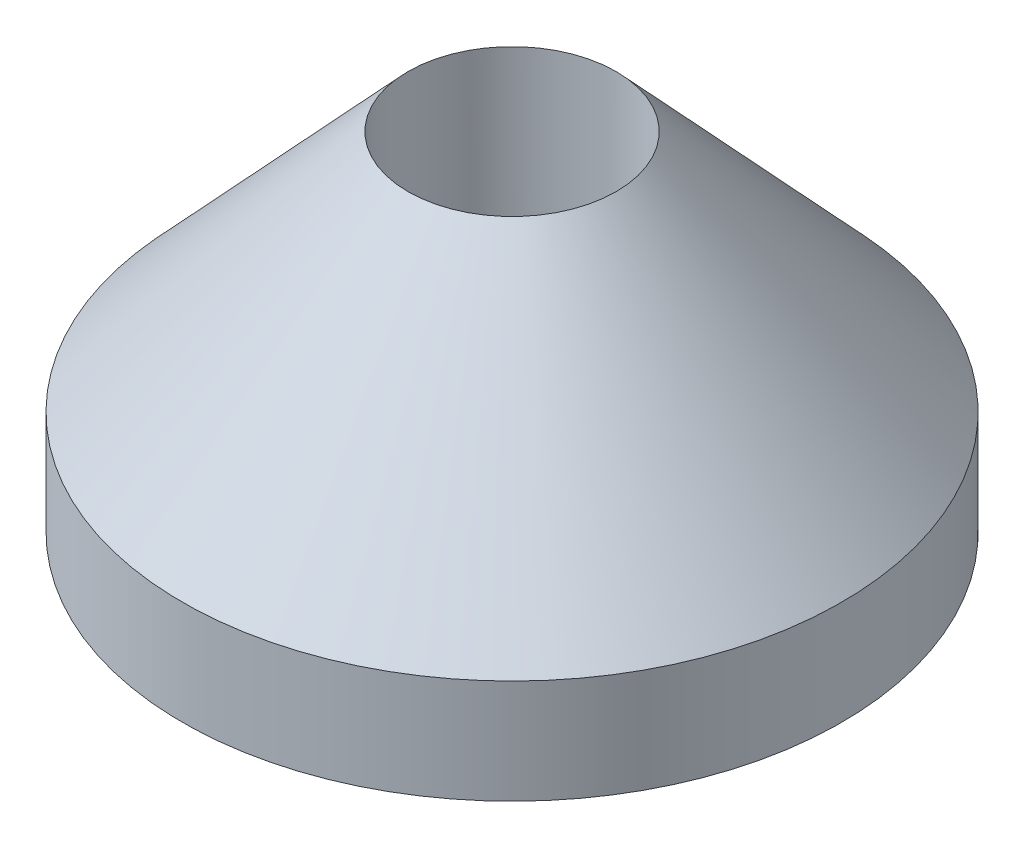
SolidWorks part; units mm, degrees
ref_plane "Front Plane" through (0, 0, 0) normal (0, 0, 1) x (1, 0, 0)
ref_plane "Top Plane" through (0, 0, 0) normal (0, 1, 0) x (1, 0, 0)
ref_plane "Right Plane" through (0, 0, 0) normal (1, 0, 0) x (0, 0, -1)
sketch "Sketch1" plane through (0, 0, 0) normal (0, 0, 1) x (1, 0, 0)
  line L0 (0, 0.5876) -> (0, 10.5876)
  line L1 (0, 0.5876) -> (9.5, 0.5876)
  line L2 (9.5, 0.5876) -> (9.5, 3.5876)
  line L3 (9.5, 3.5876) -> (3, 10.5876)
  line L4 (3, 10.5876) -> (0, 10.5876)
  dimension "D1" = 10
  dimension "D2" = 9.5
  dimension "D3" = 3
  dimension "D4" = 3
revolve "Revolve1" add sketch "Sketch1" angle 360 about L0
sketch "Sketch2" plane through (0, 10.5876, 0) normal (0, 1, 0) x (1, 0, 0)
  circle A0 centre (0, 0) radius 3
extrude "Cut-Extrude1" cut sketch "Sketch2" against normal blind 7
